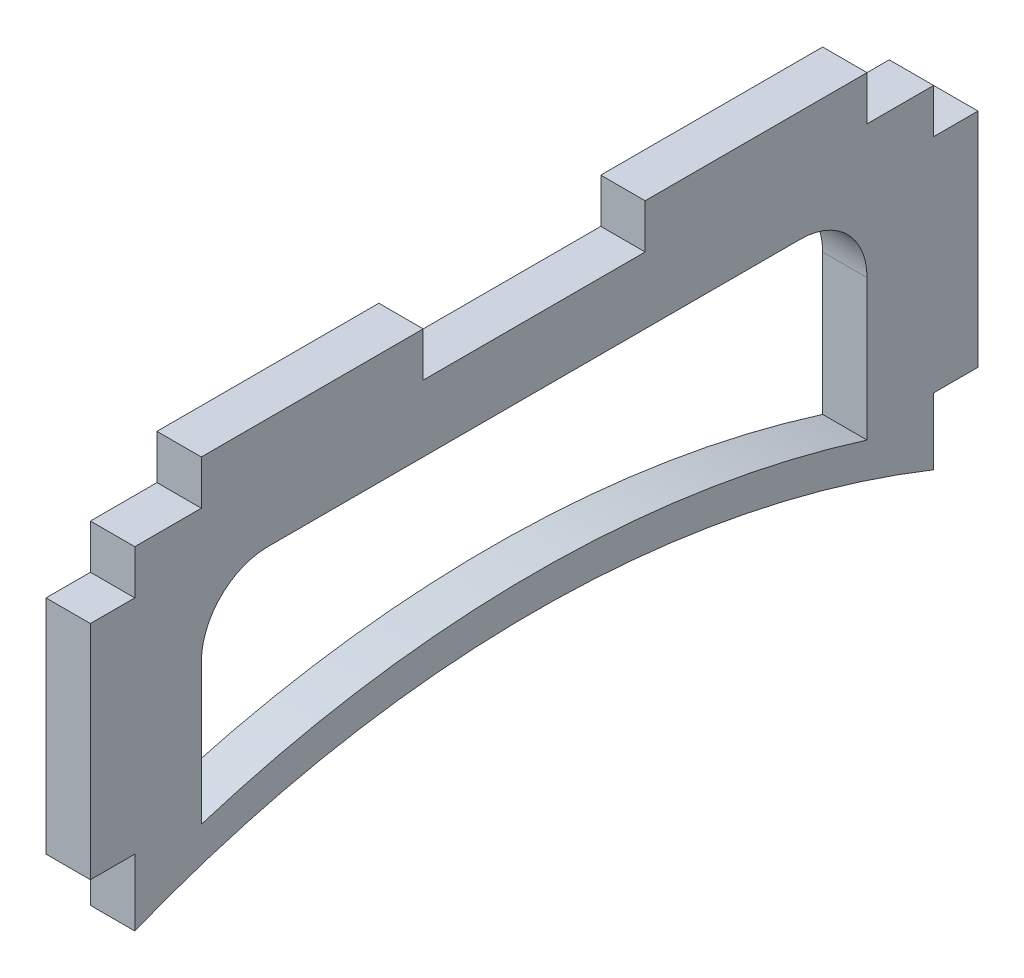
SolidWorks part; units mm, degrees
ref_plane "Front Plane" through (0, 0, 0) normal (0, 0, 1) x (1, 0, 0)
ref_plane "Top Plane" through (0, 0, 0) normal (0, 1, 0) x (1, 0, 0)
ref_plane "Right Plane" through (0, 0, 0) normal (1, 0, 0) x (0, 0, -1)
sketch "Sketch1" plane through (0, 0, 0) normal (1, 0, 0) x (0, 0, -1)
  line L0 (0, 10) -> (0, -167.3317) construction
  line L1 (-18, 0) -> (-15, 0)
  line L2 (-18, 0) -> (-18, -2)
  line L3 (-15, -12.3391) -> (-15, -6)
  line L4 (18, 0) -> (18, -2)
  line L5 (15, -6) -> (15, -12.3391)
  line L6 (-12, -3) -> (12, -3)
  line L7 (-5, 0) -> (5, 0)
  line L8 (5, 0) -> (5, 2)
  line L9 (-15, 0) -> (-15, 2)
  line L10 (-15, 2) -> (-5, 2)
  line L11 (-5, 0) -> (-5, 2)
  line L12 (15, 2) -> (5, 2)
  line L13 (15, 0) -> (15, 2)
  line L14 (15, 0) -> (18, 0)
  line L15 (-18, -2) -> (-20, -2)
  line L16 (-20, -2) -> (-20, -12)
  line L17 (-20, -12) -> (-18, -12)
  line L18 (-18, -12) -> (-18, -15)
  line L19 (18, -2) -> (20, -2)
  line L20 (20, -2) -> (20, -12)
  line L21 (20, -12) -> (18, -12)
  line L22 (18, -12) -> (18, -15)
  arc A0 (18, -15) -> (-18, -15) centre (0, -60.0361) ccw
  arc A1 (15, -12.3391) -> (-15, -12.3391) centre (0, -60.0361) ccw
  arc A2 (15, -6) -> (12, -3) centre (12, -6) ccw
  arc A3 (-12, -3) -> (-15, -6) centre (-12, -6) ccw
  dimension "D1" = 97
  dimension "D2" = 3
extrude "Boss-Extrude1" add sketch "Sketch1" along normal blind 2
